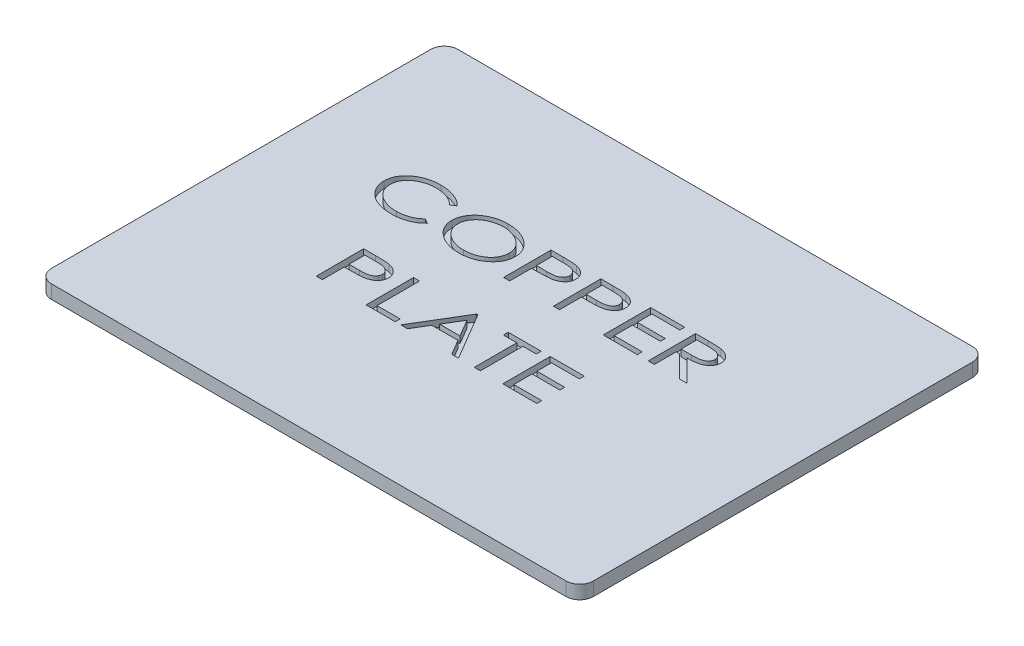
SolidWorks part; units mm, degrees
material "Copper"
ref_plane "Front Plane" through (0, 0, 0) normal (0, 0, 1) x (1, 0, 0)
ref_plane "Top Plane" through (0, 0, 0) normal (0, 1, 0) x (1, 0, 0)
ref_plane "Right Plane" through (0, 0, 0) normal (1, 0, 0) x (0, 0, -1)
sketch "Sketch1" plane through (0, 0, 0) normal (0, 1, 0) x (1, 0, 0)
  line L1 (-20, -15) -> (20, -15)
  line L2 (-20, -15) -> (-20, 15)
  line L3 (-20, 15) -> (20, 15)
  line L4 (20, -15) -> (20, 15)
  line L5 (-20, -15) -> (20, 15) construction
  line L6 (-20, 15) -> (20, -15) construction
  point P0 (0, 0)
  dimension "D1" = 30
  dimension "D2" = 40
extrude "Boss-Extrude1" add sketch "Sketch1" along normal blind 1
fillet "Fillet1" radius 1 4 edges at (-20, 0.5, -15) (20, 0.5, -15) (-20, 0.5, 15) (20, 0.5, 15)
sketch "Sketch2" plane through (0, 1, 0) normal (0, 1, 0) x (1, 0, 0)
  text T0 "COPPER \r\n  PLATE" font "Century Gothic" height 3.5
extrude "Cut-Extrude2" cut sketch "Sketch2" against normal blind 0.5
